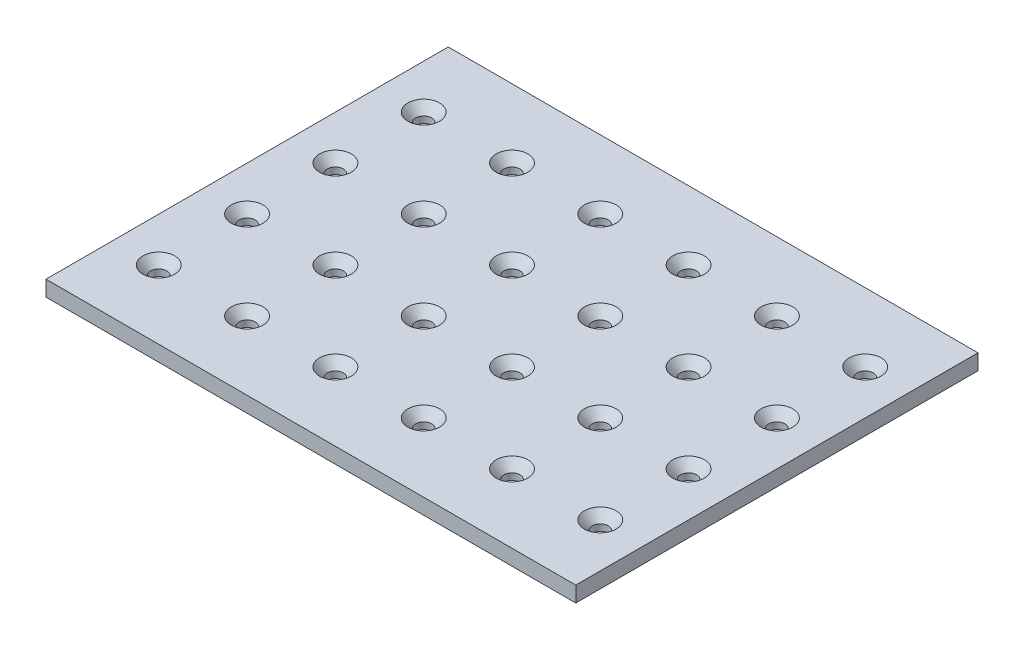
SolidWorks part; units mm, degrees
ref_plane "Front Plane" through (0, 0, 0) normal (0, 0, 1) x (1, 0, 0)
ref_plane "Top Plane" through (0, 0, 0) normal (0, 1, 0) x (1, 0, 0)
ref_plane "Right Plane" through (0, 0, 0) normal (1, 0, 0) x (0, 0, -1)
sketch "Sketch1" plane through (0, 0, 0) normal (0, 1, 0) x (1, 0, 0)
  line L1 (-54, 41) -> (54, 41)
  line L2 (-54, 41) -> (-54, -41)
  line L3 (-54, -41) -> (54, -41)
  line L4 (54, 41) -> (54, -41)
  line L5 (-54, 41) -> (54, -41) construction
  line L6 (-54, -41) -> (54, 41) construction
  circle A0 centre (-45, 27) radius 1.6319
  circle A18 centre (-27, 27) radius 1.632
  circle A19 centre (-9, 27) radius 1.632
  circle A20 centre (9, 27) radius 1.632
  circle A21 centre (27, 27) radius 1.632
  circle A22 centre (45, 27) radius 1.6319
  circle A23 centre (-27, 9) radius 1.632
  circle A24 centre (-9, 9) radius 1.632
  circle A25 centre (9, 9) radius 1.632
  circle A26 centre (27, 9) radius 1.632
  circle A27 centre (45, 9) radius 1.6319
  circle A28 centre (-27, -9) radius 1.632
  circle A29 centre (-9, -9) radius 1.632
  circle A30 centre (9, -9) radius 1.632
  circle A31 centre (27, -9) radius 1.632
  circle A32 centre (45, -9) radius 1.6319
  circle A33 centre (-27, -27) radius 1.632
  circle A34 centre (-9, -27) radius 1.632
  circle A35 centre (9, -27) radius 1.632
  circle A36 centre (27, -27) radius 1.632
  circle A37 centre (45, -27) radius 1.6319
  circle A38 centre (-45, 9) radius 1.6319
  circle A39 centre (-45, -9) radius 1.6319
  circle A40 centre (-45, -27) radius 1.6319
  point P0 (0, 0)
  dimension "D4" = 3.2639
  dimension "D8" = 18
  dimension "D9" = 18
  dimension "D1" = 108
  dimension "D2" = 82
  dimension "D3" = 9
  dimension "D5" = 14
  dimension "D6" = 6
  dimension "D7" = 4
extrude "Boss-Extrude1" add sketch "Sketch1" along normal blind 3.175
hole_wizard "CSK for #4 Flat Head Machine Screw1" positions "3DSketch2" profile "Sketch3" countersink size "#4" standard "ANSI Inch" end condition through all
sketch3d "3DSketch2"
  line L0 (45, 3.175, 27) -> (45, 0, 27) construction
  line L1 (27, 3.175, 27) -> (27, 0, 27) construction
  line L2 (9, 3.175, 27) -> (9, 0, 27) construction
  line L3 (-9, 3.175, 27) -> (-9, 0, 27) construction
  line L4 (-27, 3.175, 27) -> (-27, 0, 27) construction
  line L5 (-45, 3.175, 27) -> (-45, 0, 27) construction
  line L6 (-45, 3.175, 9) -> (-45, 0, 9) construction
  line L7 (-27, 3.175, 9) -> (-27, 0, 9) construction
  line L8 (-9, 3.175, 9) -> (-9, 0, 9) construction
  line L9 (9, 3.175, 9) -> (9, 0, 9) construction
  line L10 (27, 3.175, 9) -> (27, 0, 9) construction
  line L11 (45, 3.175, 9) -> (45, 0, 9) construction
  line L12 (45, 3.175, -9) -> (45, 0, -9) construction
  line L13 (27, 3.175, -9) -> (27, 0, -9) construction
  line L14 (9, 3.175, -9) -> (9, 0, -9) construction
  line L15 (-9, 3.175, -9) -> (-9, 0, -9) construction
  line L16 (-27, 3.175, -9) -> (-27, 0, -9) construction
  line L17 (-45, 3.175, -9) -> (-45, 0, -9) construction
  line L18 (-45, 3.175, -27) -> (-45, 0, -27) construction
  line L19 (-27, 3.175, -27) -> (-27, 0, -27) construction
  line L20 (-9, 3.175, -27) -> (-9, 0, -27) construction
  line L21 (9, 3.175, -27) -> (9, 0, -27) construction
  line L22 (27, 3.175, -27) -> (27, 0, -27) construction
  line L23 (45, 3.175, -27) -> (45, 0, -27) construction
  point P0 (45, 3.175, 27)
  point P4 (27, 3.175, 27)
  point P8 (9, 3.175, 27)
  point P12 (-9, 3.175, 27)
  point P16 (-27, 3.175, 27)
  point P20 (-45, 3.175, 27)
  point P24 (-45, 3.175, 9)
  point P28 (-27, 3.175, 9)
  point P32 (-9, 3.175, 9)
  point P36 (9, 3.175, 9)
  point P40 (27, 3.175, 9)
  point P44 (45, 3.175, 9)
  point P48 (45, 3.175, -9)
  point P52 (27, 3.175, -9)
  point P56 (9, 3.175, -9)
  point P60 (-9, 3.175, -9)
  point P64 (-27, 3.175, -9)
  point P68 (-45, 3.175, -9)
  point P72 (-45, 3.175, -27)
  point P76 (-27, 3.175, -27)
  point P80 (-9, 3.175, -27)
  point P84 (9, 3.175, -27)
  point P88 (27, 3.175, -27)
  point P92 (45, 3.175, -27)
sketch "Sketch3" plane through (45, 3.175, 27) normal (1, 0, 0) x (0, 0, 1)
  line L0 (0, 0) -> (0, 3.175)
  line L1 (0, 3.175) -> (1.6319, 3.175)
  line L2 (1.6319, 3.175) -> (1.6319, 1.8481)
  line L3 (1.6319, 1.8481) -> (3.2385, 0)
  line L5 (3.2385, 0) -> (0, 0)
  line L6 (-1.632, 1.8481) -> (-3.2385, 0) construction
  line L11 (0, -6.35) -> (0, 107.95) construction
  dimension "Thru Hole Dia." = 3.2639
  dimension "Thru Hole Depth" = 3.175
  dimension "Near C'Sink Dia." = 6.477
  dimension "Near C'Sink Angle" = 82
